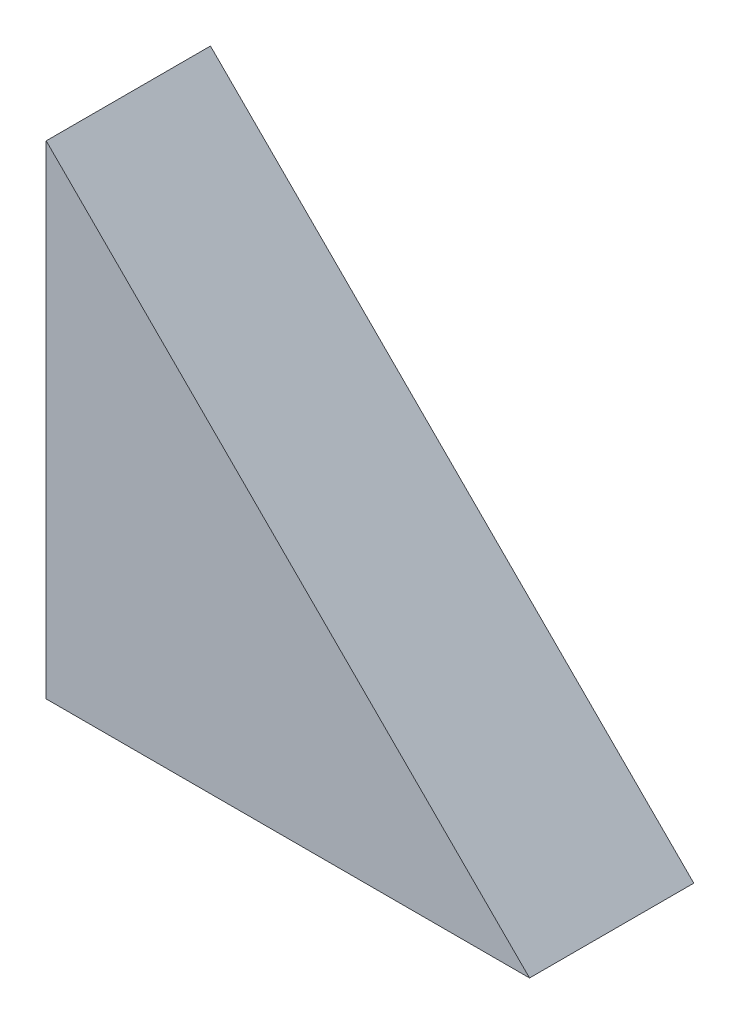
SolidWorks part; units mm, degrees
ref_plane "Front Plane" through (0, 0, 0) normal (0, 0, 1) x (1, 0, 0)
ref_plane "Top Plane" through (0, 0, 0) normal (0, 1, 0) x (1, 0, 0)
ref_plane "Right Plane" through (0, 0, 0) normal (1, 0, 0) x (0, 0, -1)
sketch "Sketch3" plane through (0, 0, 0) normal (0, 0, 1) x (1, 0, 0)
  line L0 (0, 0) -> (103, 0)
  line L1 (103, 0) -> (0, 103)
  line L2 (0, 103) -> (0, 0)
  dimension "D1" = 103
extrude "Boss-Extrude1" add sketch "Sketch3" along normal blind 35
